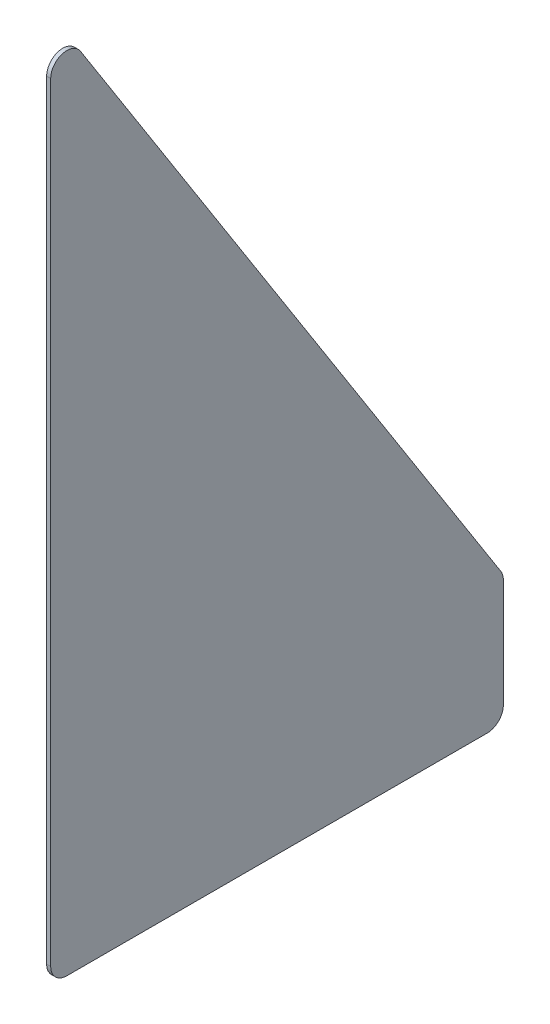
SolidWorks part; units mm, degrees
material "PC High Viscosity"
ref_plane "Front Plane" through (0, 0, 0) normal (0, 0, 1) x (1, 0, 0)
ref_plane "Top Plane" through (0, 0, 0) normal (0, 1, 0) x (1, 0, 0)
ref_plane "Right Plane" through (0, 0, 0) normal (1, 0, 0) x (0, 0, -1)
sketch "Sketch1" plane through (0, 0, 0) normal (0, 1, 0) x (1, 0, 0)
  line L0 (0, 0) -> (0, 177.8)
  line L1 (0, 177.8) -> (1.5875, 177.8)
  line L2 (1.5875, 177.8) -> (1.5875, 0)
  line L5 (1.5875, 0) -> (0, 0)
  dimension "D2" = 177.8
  dimension "D4" = 1.5875
extrude "Boss-Extrude1" add sketch "Sketch1" along normal blind 330.2
sketch "Sketch2" plane through (0, 0, 0) normal (-1, 0, 0) x (0, 0, 1)
  line L0 (-177.8, 50.8) -> (0, 330.2)
  line L1 (0, 330.2) -> (-177.8, 330.2)
  line L2 (-177.8, 330.2) -> (-177.8, 50.8)
  line L4 (-177.8, 330.2) -> (-177.8, 0) construction
  line L5 (-177.8, 330.2) -> (0, 330.2) construction
  line L6 (0, 330.2) -> (0, 0) construction
  dimension "D2" = 50.8
extrude "Cut-Extrude1" cut sketch "Sketch2" against normal up to surface (1.5875 mm away) up to face at (1.5875, 165.1, -88.9)
fillet "Fillet1" radius 6.35 4 edges at (0.7937, 0, -177.8) (0.7937, 0, 0) (0.7937, 330.2, 0) (0.7937, 50.8, -177.8)
